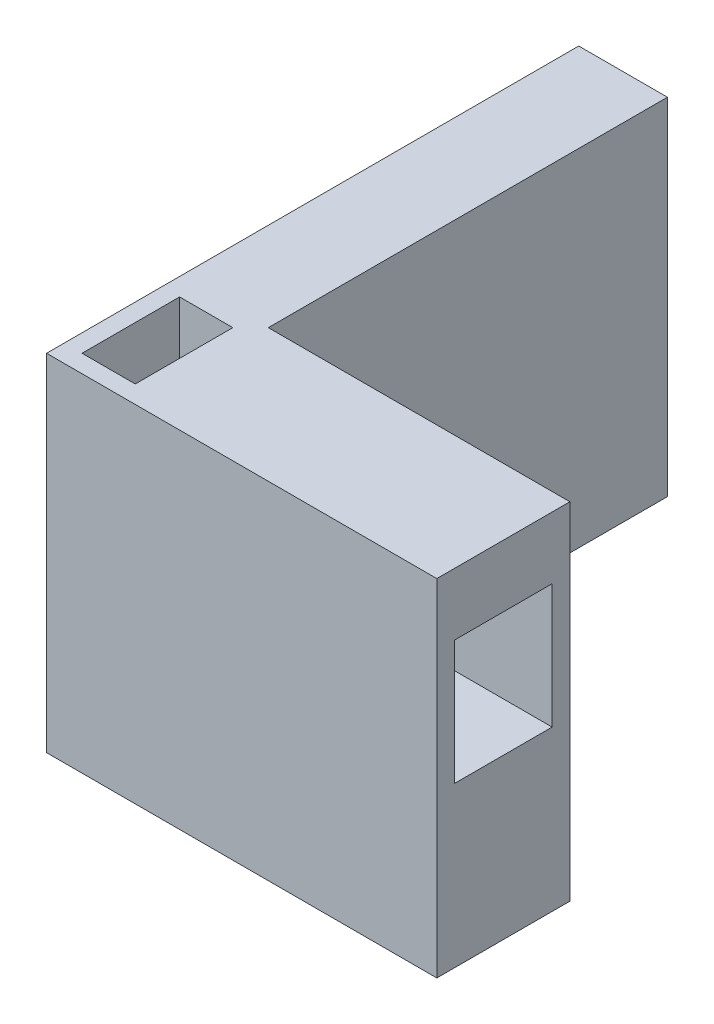
SolidWorks part; units mm, degrees
ref_plane "Front Plane" through (0, 0, 0) normal (0, 0, 1) x (1, 0, 0)
ref_plane "Top Plane" through (0, 0, 0) normal (0, 1, 0) x (1, 0, 0)
ref_plane "Right Plane" through (0, 0, 0) normal (1, 0, 0) x (0, 0, -1)
sketch "Sketch1" plane through (0, 0, 0) normal (0, 1, 0) x (1, 0, 0)
  line L0 (0, 0) -> (440, 0)
  line L1 (440, 0) -> (440, 150)
  line L2 (440, 150) -> (100, 150)
  line L3 (100, 150) -> (100, 600)
  line L4 (100, 600) -> (0, 600)
  line L5 (0, 600) -> (0, 0)
  dimension "D1" = 440
  dimension "D2" = 150
  dimension "D3" = 100
  dimension "D4" = 600
extrude "Boss-Extrude5" add sketch "Sketch1" along normal blind 390
sketch "Sketch7" plane through (0, 0, -150) normal (0, 0, -1) x (-1, 0, 0)
  line L0 (-440, 390) -> (-440, 250)
  line L1 (-440, 390) -> (-440, 0) construction
  line L2 (-440, 250) -> (-190, 250)
  line L3 (-440, 0) -> (-100, 0) construction
  circle A0 centre (-190, 250) radius 30
  dimension "D3" = 60
  dimension "D1" = 250
  dimension "D2" = 250
extrude "Cut-Extrude4" cut sketch "Sketch7" against normal blind 120
sketch "Sketch9" plane through (0, 0, -150) normal (0, 0, -1) x (-1, 0, 0)
  line L0 (-190, 250) -> (-440, 250)
  line L1 (-440, 390) -> (-440, 0) construction
sketch "Sketch10" plane through (440, 0, 0) normal (1, 0, 0) x (0, 0, -1)
  line L0 (150, 250) -> (0, 250)
  line L1 (0, 390) -> (0, 0) construction
  line L2 (130, 180) -> (130, 320)
  line L4 (150, 250) -> (150, 180)
  line L5 (150, 180) -> (0, 180)
  line L6 (0, 250) -> (0, 180)
  line L8 (150, 250) -> (150, 320)
  line L9 (150, 320) -> (0, 320)
  line L10 (0, 250) -> (0, 320)
  line L11 (20, 180) -> (20, 320)
  line M7 (150, 0) -> (150, 390)
  line M9 (0, 390) -> (0, 0)
  dimension "D1" = 70
  dimension "D2" = 70
  dimension "D3" = 20
  dimension "D4" = 20
extrude "Cut-Extrude6" cut sketch "Sketch10" against normal through all contours L9 L0 M7 M9 | L5 L0 M7 M9
sketch "Sketch13" plane through (0, 0, 0) normal (0, -1, 0) x (1, 0, 0)
  line L0 (50, -600) -> (50, 0)
  line L1 (100, -600) -> (0, -600) construction
  line L2 (0, 0) -> (440, 0) construction
  line L4 (50, 0) -> (100, 0)
  line L5 (50, 0) -> (50, -150)
  line L6 (50, -150) -> (100, -150)
  line L7 (100, 0) -> (100, -150)
  line L8 (50, -150) -> (0, -150)
  line L9 (50, -150) -> (50, 0)
  line L10 (50, 0) -> (0, 0)
  line L11 (0, -150) -> (0, 0)
  line L12 (80, -130) -> (20, -130)
  line L13 (80, -130) -> (80, -20)
  line L14 (80, -20) -> (20, -20)
  line L15 (20, -130) -> (20, -20)
  line L16 (80, -130) -> (20, -20) construction
  line L17 (80, -20) -> (20, -130) construction
  point P12 (50, -75)
  dimension "D1" = 20
  dimension "D2" = 20
extrude "Cut-Extrude9" cut sketch "Sketch13" against normal up to surface (390 mm away) contours L13 L14 L9 L12 | L15 L12 L9 L14
sketch "Sketch14" plane through (0, 0, -150) normal (0, 0, -1) x (-1, 0, 0)
  line L0 (-190, 250) -> (-100, 250)
  line L1 (-100, 390) -> (-100, 0) construction
  line L2 (-100, 250) -> (0, 250)
  line L3 (0, 390) -> (0, 0) construction
sketch "Sketch15" plane through (0, 0, -600) normal (0, 0, -1) x (-1, 0, 0)
  line L0 (-100, 250) -> (0, 250) construction
  line L1 (-80, 280) -> (-20, 280)
  line L2 (-80, 280) -> (-80, 220)
  line L3 (-80, 220) -> (-20, 220)
  line L4 (-20, 280) -> (-20, 220)
  line L5 (-80, 280) -> (-20, 220) construction
  line L6 (-80, 220) -> (-20, 280) construction
  point P0 (-50, 250)
  dimension "D1" = 60
  dimension "D2" = 60
extrude "Cut-Extrude10" cut sketch "Sketch15" against normal up to surface (470 mm away) up to face at (106.6667, 231.6667, -130)
